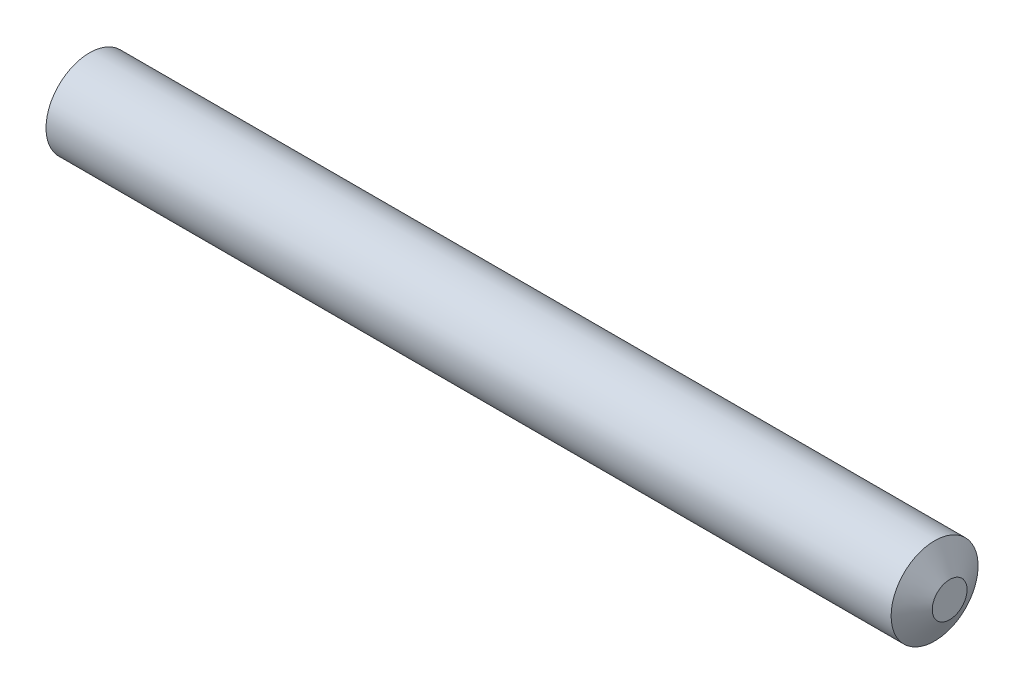
SolidWorks part; units mm, degrees
ref_plane "Plane1" through (0, 0, 0) normal (0, 0, 1) x (1, 0, 0)
ref_plane "Plane2" through (0, 0, 0) normal (0, 1, 0) x (1, 0, 0)
ref_plane "Plane3" through (0, 0, 0) normal (1, 0, 0) x (0, 0, -1)
sketch "BodySke" plane through (0, 0, 0) normal (0, 0, 1) x (1, 0, 0)
  line L0 (0, 0) -> (0, 0.774)
  line L1 (0, 0.774) -> (0.2748, 1.25)
  line L2 (0.2748, 1.25) -> (24.567, 1.25)
  line L3 (24.567, 1.25) -> (25, 0.5)
  line L4 (25, 0) -> (0, 0)
  line L5 (-12.7, 0) -> (88.9, 0) construction
  line L6 (25, 0.5) -> (25, 0)
  line L7 (25, 0.5) -> (25, 10.025) construction
  line L8 (0, -0.774) -> (0.2748, -1.25) construction
  line L9 (0.4, 15.875) -> (0.4, -3.175) construction
  line L10 (24.567, -1.25) -> (25, -0.5) construction
  dimension "Length" = 25
  dimension "Diameter" = 2.5
  dimension "Drive_ch_ang" = 60
  dimension "Minor_dia" = 1.548
  dimension "Cup_nose_ang" = 30
  dimension "Cup_dia" = 1
  dimension "Advance" = 0.4
revolve "BaseBody" add sketch "BodySke" angle 360 about L5
cosmetic thread "ThreadCosmetic" [suppressed] parameters "Thread_minor"=1.548
sketch "Sketch2" plane through (0, 0, 0) normal (-1, 0, 0) x (0, 0, 1)
  line L0 (0.2598, 0.45) -> (-0.2598, 0.45)
  line L1 (-0.2598, 0.45) -> (-0.5196, 0)
  line L2 (0.2598, 0.45) -> (0.5196, 0)
  line L3 (0.2598, -0.45) -> (0.5196, 0)
  line L4 (0.2598, -0.45) -> (-0.2598, -0.45)
  line L5 (-0.2598, -0.45) -> (-0.5196, 0)
  dimension "Hex_size" = 0.9
  dimension "D2" = 0.45
  dimension "D3" = 0.45
extrude "Hex" cut sketch "Sketch2" against normal blind 0.6
sketch "Sketch4" plane through (0, 4.7709, -0.5249) normal (-1, 0, 0) x (0, 0, 1)
  line L0 (0.5249, -4.7709) -> (0.9694, -4.7709)
  line L1 (0.5249, -4.7709) -> (5.545, 0.2492) construction
  line L2 (0.5249, -4.7709) -> (0.5249, -4.3264)
  line L3 (0.8397, -4.6718) -> (0.928, -4.5835)
  line L4 (0.624, -4.4561) -> (0.7123, -4.3678)
  arc A0 (0.8397, -4.6718) -> (0.624, -4.4561) centre (0.5249, -4.7709) ccw
  arc A1 (0.9694, -4.7709) -> (0.928, -4.5835) centre (0.5249, -4.7709) ccw
  arc A2 (0.5249, -4.3264) -> (0.7123, -4.3678) centre (0.5249, -4.7709) cw
  circle A3 centre (0.5249, -4.7709) radius 0.33 construction
  circle A4 centre (0.5249, -4.7709) radius 0.4445 construction
  dimension "D1" = 45
  dimension "Spline_n_dim" = 0.66
  dimension "Spline_m_dim" = 0.889
  dimension "Spline_a_dim" = 90
  dimension "D3" = 0.1525
  dimension "Spline_p_dim" = 0.305
extrude "Spline6" [suppressed] cut sketch "Sketch4" against normal blind 0.6
pattern_circular "CirPattern1" [suppressed] count 4 every 90 about axis through (-12.7, 0, 0) along (1, 0, 0)
sketch "Sketch5" plane through (0, 0.6556, 6.6316) normal (-1, 0, 0) x (0, 0, 1)
  line L0 (-6.6316, -0.6556) -> (-6.1871, -0.6556)
  line L1 (-6.6316, -0.6556) -> (-1.6115, 4.3645) construction
  line L2 (-6.6316, -0.6556) -> (-6.6316, -0.2111)
  line L3 (-6.2904, -0.5301) -> (-6.2286, -0.4682)
  line L4 (-6.5061, -0.3144) -> (-6.4442, -0.2525)
  line L5 (-6.5061, -0.3144) -> (-6.2904, -0.5301)
  arc A1 (-6.1871, -0.6556) -> (-6.2286, -0.4682) centre (-6.6316, -0.6556) ccw
  arc A2 (-6.6316, -0.2111) -> (-6.4442, -0.2525) centre (-6.6316, -0.6556) cw
  circle A3 centre (-6.6316, -0.6556) radius 0.33 construction
  circle A4 centre (-6.6316, -0.6556) radius 0.4445 construction
  dimension "D1" = 45
  dimension "Spline_n_dim" = 0.66
  dimension "Spline_m_dim" = 0.889
  dimension "Spline_a_dim" = 90
  dimension "D3" = 0.1525
  dimension "Spline_p_dim" = 0.305
extrude "Spline4" [suppressed] cut sketch "Sketch5" against normal blind 0.6
pattern_circular "CirPattern2" [suppressed] count 4 every 90 about axis through (-12.7, 0, 0) along (1, 0, 0)
sketch "ThdSchSke" plane through (0, 0, 0) normal (0, 0, 1) x (1, 0, 0)
  line L0 (0.2748, -0.774) -> (-0.0585, -1.25)
  line L1 (0.2748, -0.774) -> (0.6081, -1.25)
  line L2 (0.6081, -1.25) -> (0.6081, -1.5625)
  line L3 (-3.175, 0) -> (5.1513, 0) construction
  line L4 (0.2748, 1.25) -> (0.2748, -1.25) construction
  line L5 (0.6081, -1.5625) -> (-0.0585, -1.5625)
  line L6 (-0.0585, -1.5625) -> (-0.0585, -1.25)
  dimension "Thread_minor" = 1.548
  dimension "Diameter" = 2.5
  dimension "SideAngle" = 55
  dimension "VeeAngle" = 70
  dimension "Overcut" = 3.125
revolve "ThreadSchematic" [suppressed] cut sketch "ThdSchSke" angle 360 about L3
pattern_linear "ThdSchPat" [suppressed]
equation "\"D2@Sketch2\" = \"Hex_size@Sketch2\" / 2"
equation "\"D3@Sketch2\" = \"Hex_size@Sketch2\" / 2"
equation "\"Thread_minor@ThreadCosmetic\" = \"Minor_dia@BodySke\""
equation "\"D1@Sketch4\" = \"Spline_a_dim@Sketch4\" / 2"
equation "\"D3@Sketch4\" = \"Spline_p_dim@Sketch4\" / 2"
equation "\"D2@CirPattern1\" = \"Spline_a_dim@Sketch4\""
equation "\"Num_teeth@CirPattern1\" = 360 / \"D2@CirPattern1\""
equation "\"Spline_a_dim@Sketch5\" = 90"
equation "\"Spline_p_dim@Sketch5\" = \"Spline_p_dim@Sketch4\""
equation "\"Spline_m_dim@Sketch5\" = \"Spline_m_dim@Sketch4\""
equation "\"Spline_n_dim@Sketch5\" = \"Spline_n_dim@Sketch4\""
equation "\"D1@Sketch5\" = \"Spline_a_dim@Sketch5\" / 2"
equation "\"D3@Sketch5\" = \"Spline_p_dim@Sketch5\" / 2"
equation "\"Key_eng@Spline4\" = \"Key_eng@Spline6\""
equation "\"Thread_minor@ThdSchSke\" = \"Thread_minor@ThreadCosmetic\""
equation "\"Diameter@ThdSchSke\" = \"Diameter@BodySke\""
equation "\"Overcut@ThdSchSke\" = \"Diameter@BodySke\" * 1.25"
equation "\"Num_threads@ThdSchPat\" = int( (\"Length@BodySke\" - ( ( ( \"Diameter@BodySke\" - \"Minor_dia@BodySke\" ) * 0.5 ) / tan( \"Drive_ch_ang@BodySke\" * 0.017453292 ) ) - ( ( ( \"Diameter@BodySke\" - \"Cup_dia@BodySke\" ) * 0.5 ) * tan( \"Cup_nose_ang@BodySke\" * 0.017453292 ) ) ) / \"Advance@BodySke\" + 0.999 )  + 1"
equation "\"Advance@ThdSchPat\" = (\"Length@BodySke\" - ( ( ( \"Diameter@BodySke\" - \"Minor_dia@BodySke\" ) * 0.5 ) / tan( \"Drive_ch_ang@BodySke\" * 0.017453292 ) ) - ( ( ( \"Diameter@BodySke\" - \"Cup_dia@BodySke\" ) * 0.5 ) * tan( \"Cup_nose_ang@BodySke\" * 0.017453292 ) ) ) /  (\"Num_threads@ThdSchPat\" - 1) 'relax it"
equation "' \"Num_threads@ThdSchPat\" = \"Num_threads@ThdSchPat\" - sgn( \"Num_threads@ThdSchPat\" - 1) '---chamfered tips only---"
